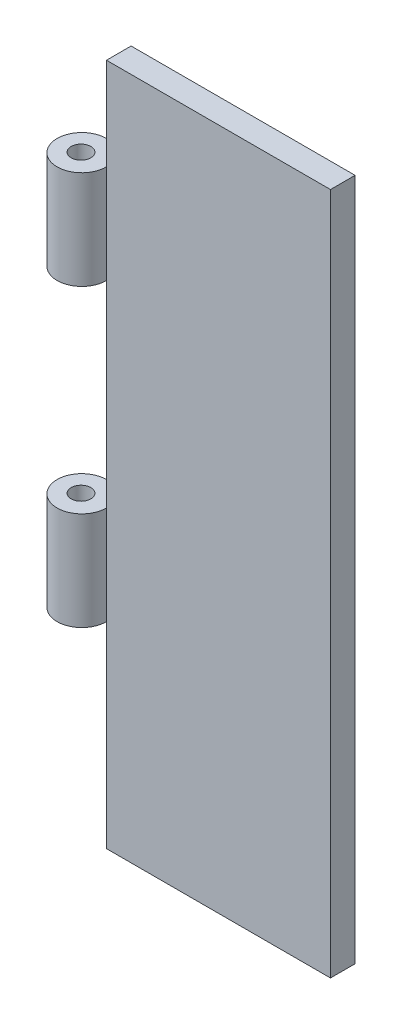
SolidWorks part; units mm, degrees
ref_plane "前视基准面" through (0, 0, 0) normal (0, 0, 1) x (1, 0, 0)
ref_plane "上视基准面" through (0, 0, 0) normal (0, 1, 0) x (1, 0, 0)
ref_plane "右视基准面" through (0, 0, 0) normal (1, 0, 0) x (0, 0, -1)
other "Configuration Table"
sketch "草图1" plane through (0, 0, 0) normal (0, 0, 1) x (1, 0, 0)
  line L0 (0, 0) -> (0, 68.7593)
  line L1 (0, 68.7593) -> (-45.4941, 68.7593)
  line L2 (-45.4941, 68.7593) -> (-45.4941, -69.9306)
  line L3 (-45.4941, -69.9306) -> (0, -69.9306)
  line L4 (0, -69.9306) -> (0, 0)
extrude "凸台-拉伸1" add sketch "草图1" along normal blind 5
ref_plane "基准面1" through (0, 30, 0) normal (0, 1, 0) x (1, 0, 0)
sketch "草图2" plane through (0, 30, 0) normal (0, 1, 0) x (1, 0, 0)
  line L0 (-45.4941, 0) -> (-50.5026, 0)
  line L1 (-156.0175, 0) -> (156.0175, 0) construction
  line L2 (-45.4941, -5) -> (-45.4941, 0) construction
  line L3 (0, -5) -> (-45.4941, -5) construction
  line L4 (-45.4941, -5) -> (-45.4941, 0)
  arc A0 (-50.5026, 0) -> (-45.4941, -5) centre (-50.5026, -5.0086) ccw
extrude "凸台-拉伸2" add sketch "草图2" along normal blind 20
ref_plane "基准面2" through (0, 10, 0) normal (0, 1, 0) x (1, 0, 0)
mirror "镜向2" about plane through (0, 10, 0) normal (0, 1, 0) of "凸台-拉伸2"
sketch "草图4" plane through (0, 50, 0) normal (0, 1, 0) x (1, 0, 0)
  circle A0 centre (-50.6789, -4.9958) radius 2
extrude "切除-拉伸1" cut sketch "草图4" against normal through all
